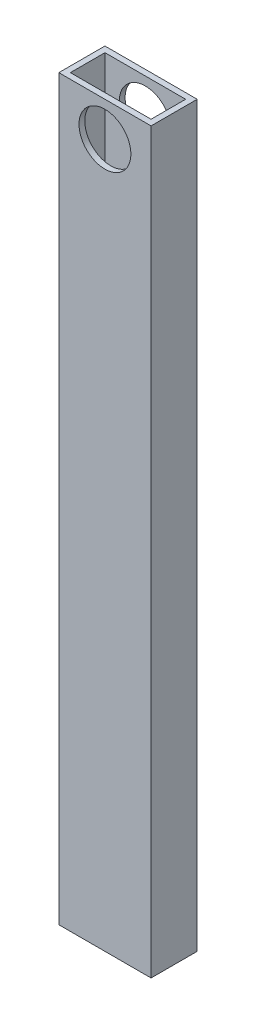
SolidWorks part; units mm, degrees
ref_plane "Front Plane" through (0, 0, 0) normal (0, 0, 1) x (1, 0, 0)
ref_plane "Top Plane" through (0, 0, 0) normal (0, 1, 0) x (1, 0, 0)
ref_plane "Right Plane" through (0, 0, 0) normal (1, 0, 0) x (0, 0, -1)
sketch "Sketch1" plane through (0, 0, 0) normal (0, 1, 0) x (1, 0, 0)
  line L1 (-25.4, 12.7) -> (25.4, 12.7)
  line L2 (-25.4, 12.7) -> (-25.4, -12.7)
  line L3 (-25.4, -12.7) -> (25.4, -12.7)
  line L4 (25.4, 12.7) -> (25.4, -12.7)
  line L5 (-25.4, 12.7) -> (25.4, -12.7) construction
  line L6 (-25.4, -12.7) -> (25.4, 12.7) construction
  point P0 (0, 0)
  dimension "D1" = 25.4
  dimension "D2" = 50.8
extrude "Boss-Extrude1" add sketch "Sketch1" along normal blind 406.4
shell "Shell1" thickness 3.175
sketch "Sketch2" plane through (0, 0, 12.7) normal (0, 0, 1) x (1, 0, 0)
  line L0 (-25.4, 406.4) -> (25.4, 406.4) construction
  line L1 (25.4, 406.4) -> (25.4, 0) construction
  circle A0 centre (0, 387.35) radius 14.2875
  point P6 (0.5024, 387.6085)
  dimension "D1" = 28.575
  dimension "D2" = 19.05
  dimension "D3" = 25.4
extrude "Cut-Extrude1" cut sketch "Sketch2" against normal blind 406.4
